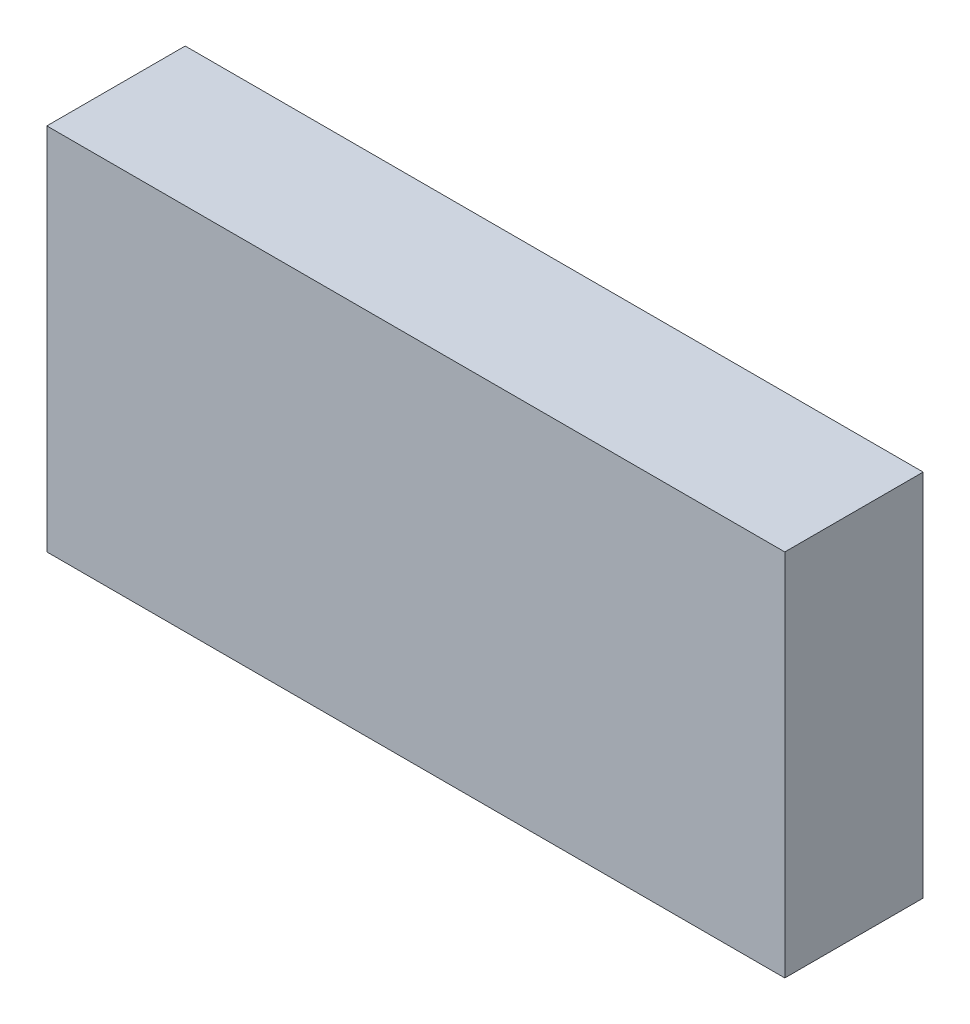
SolidWorks part; units mm, degrees
ref_plane "Front Plane" through (0, 0, 0) normal (0, 0, 1) x (1, 0, 0)
ref_plane "Top Plane" through (0, 0, 0) normal (0, 1, 0) x (1, 0, 0)
ref_plane "Right Plane" through (0, 0, 0) normal (1, 0, 0) x (0, 0, -1)
sketch "Sketch1" plane through (0, 0, 0) normal (0, 0, 1) x (1, 0, 0)
  line L1 (-40, -20) -> (40, -20)
  line L2 (-40, -20) -> (-40, 20)
  line L3 (-40, 20) -> (40, 20)
  line L4 (40, -20) -> (40, 20)
  line L5 (-40, -20) -> (40, 20) construction
  line L6 (-40, 20) -> (40, -20) construction
  point P0 (0, 0)
  dimension "D1" = 40
  dimension "D2" = 80
extrude "Boss-Extrude1" add sketch "Sketch1" along normal blind 15
sketch "Sketch2" plane through (0, 0, 15) normal (0, 0, 1) x (1, 0, 0)
  line L0 (-27, -14) -> (3.6923, 16.6923) construction
  line L1 (-40, -20) -> (40, -20) construction
  line L2 (0, 0) -> (0, -50000) construction
  line L3 (-707.1068, -721.1068) -> (34648.2323, 34634.2323) construction
  line L4 (-707.1068, 693.1068) -> (34648.2323, -34662.2323) construction
  line L5 (-680.1068, 693.1068) -> (34675.2323, -34662.2323) construction
  circle A0 centre (0, -14) radius 12
  circle A1 centre (27, -14) radius 12
  circle A2 centre (0, -14) radius 11 construction
  circle A3 centre (27, -14) radius 11 construction
  circle A4 centre (-27, -14) radius 12
  circle A5 centre (-27, -14) radius 11 construction
  point P7 (0, -26)
  point P15 (-13.5, -0.5)
  point P24 (13.5, -0.5)
  dimension "D1" = 24
  dimension "D2" = 6
  dimension "D3" = 27
  dimension "D4" = 22
  dimension "D5" = 27
  dimension "D6" = 45
